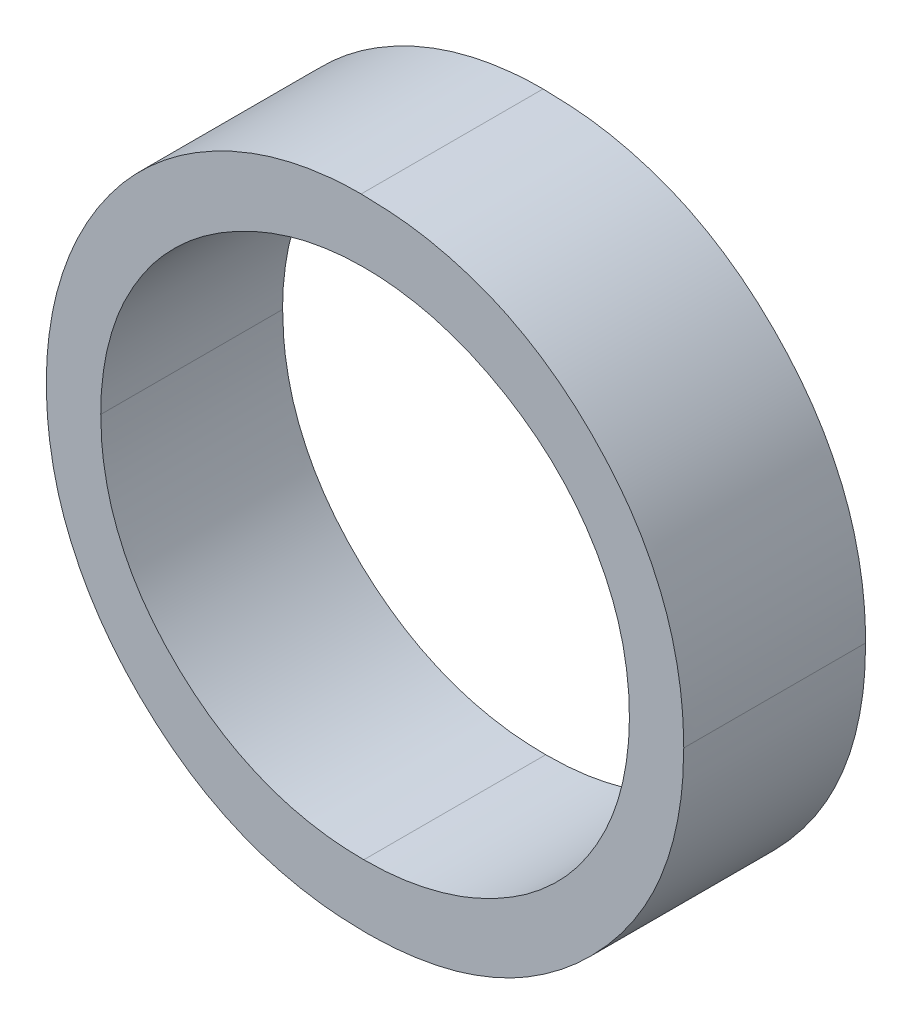
SolidWorks part; units mm, degrees
ref_plane "Plan de face" through (0, 0, 0) normal (0, 0, 1) x (1, 0, 0)
ref_plane "Plan de dessus" through (0, 0, 0) normal (0, 1, 0) x (1, 0, 0)
ref_plane "Plan de droite" through (0, 0, 0) normal (1, 0, 0) x (0, 0, -1)
sketch "Esquisse1" plane through (0, 0, 0) normal (0, 0, 1) x (1, 0, 0)
  text T0 "O" font "Century Gothic" height 5
extrude "Boss.-Extru.1" add sketch "Esquisse1" along normal blind 1.5
